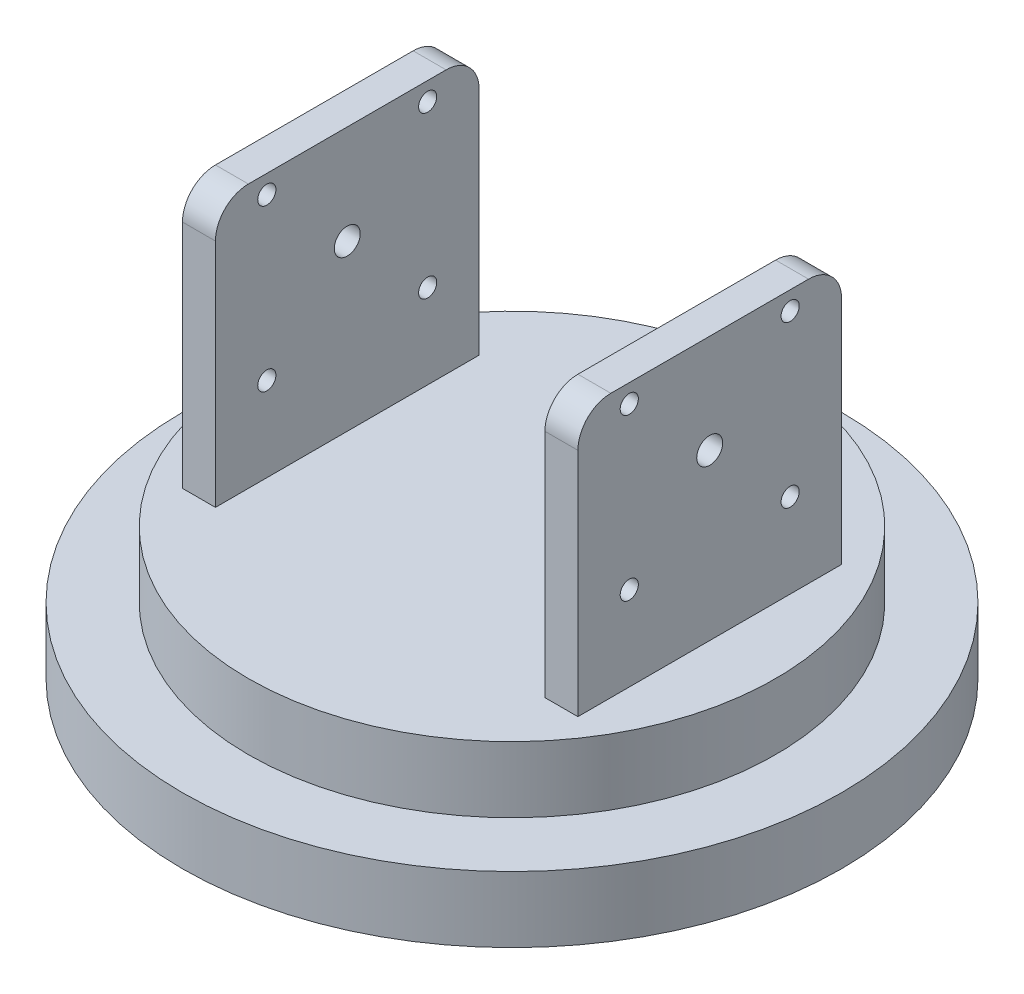
SolidWorks part; units mm, degrees
material "Plain Carbon Steel"
ref_plane "Front Plane" through (0, 0, 0) normal (0, 0, 1) x (1, 0, 0)
ref_plane "Top Plane" through (0, 0, 0) normal (0, 1, 0) x (1, 0, 0)
ref_plane "Right Plane" through (0, 0, 0) normal (1, 0, 0) x (0, 0, -1)
sketch "Sketch2" plane through (0, 0, 0) normal (0, 1, 0) x (1, 0, 0)
  circle A1 centre (0, 0) radius 63.5
  dimension "D2" = 127
extrude "Boss-Extrude1" add sketch "Sketch2" along normal blind 12.7
sketch "Sketch3" plane through (0, 12.7, 0) normal (0, 1, 0) x (1, 0, 0)
  circle A0 centre (0, 0) radius 50.8
  dimension "D1" = 101.6
extrude "Boss-Extrude2" add sketch "Sketch3" along normal blind 12.7
sketch "Sketch4" plane through (0, 0, 0) normal (0, -1, 0) x (1, 0, 0)
  circle A0 centre (0, 0) radius 6.35
  dimension "D1" = 12.7
extrude "Boss-Extrude3" add sketch "Sketch4" along normal blind 25.4
sketch "Sketch5" plane through (0, 25.4, 0) normal (0, 1, 0) x (1, 0, 0)
  line L0 (0, 0) -> (0, 17.7689) construction
  line L1 (38.1, -25.4) -> (31.75, -25.4)
  line L2 (-38.1, 25.4) -> (-31.75, 25.4)
  line L3 (-38.1, 25.4) -> (-38.1, -25.4)
  line L4 (-38.1, -25.4) -> (-31.75, -25.4)
  line L5 (-31.75, 25.4) -> (-31.75, -25.4)
  line L6 (31.75, 25.4) -> (31.75, -25.4)
  line L7 (38.1, 25.4) -> (31.75, 25.4)
  line L8 (38.1, 25.4) -> (38.1, -25.4)
  dimension "D1" = 6.35
  dimension "D2" = 50.8
  dimension "D3" = 25.4
  dimension "D4" = 31.75
extrude "Boss-Extrude4" add sketch "Sketch5" along normal blind 50.8
fillet "Fillet1" radius 6.35 4 edges at (34.925, 76.2, 25.4) (-34.925, 76.2, 25.4) (34.925, 76.2, -25.4) (-34.925, 76.2, -25.4)
sketch "Sketch6" plane through (-38.1, 0, 0) normal (-1, 0, 0) x (0, 0, 1)
  line L0 (-19.05, 76.2) -> (19.05, 76.2) construction
  line L1 (25.4, 69.85) -> (25.4, 25.4) construction
  circle A0 centre (0, 57.15) radius 2.5019
  circle A1 centre (-15.5, 41.65) radius 1.75
  circle A2 centre (15.5, 41.65) radius 1.75
  circle A3 centre (15.5, 72.65) radius 1.75
  circle A4 centre (-15.5, 72.65) radius 1.75
  dimension "D1" = 5.0038
  dimension "D2" = 19.05
  dimension "D3" = 25.4
  dimension "D5" = 15.5
  dimension "D6" = 15.5
  dimension "D7" = 3.5
  dimension "D10" = 31
  dimension "D11" = 31
  dimension "D12" = 9.9
  dimension "D8" = 2
  dimension "D9" = 2
extrude "Cut-Extrude1" cut sketch "Sketch6" against normal through all
sketch "Sketch7" plane through (0, -25.4, 0) normal (0, -1, 0) x (1, 0, 0)
  line L7 (0, 0) -> (0, 6.35) construction
  line L8 (0, 5.08) -> (0.7102, 6.3102)
  line L9 (0, 5.08) -> (-0.7102, 6.3102)
  arc A6 (0.7102, 6.3102) -> (-0.7102, 6.3102) centre (0, 0) ccw
  dimension "D1" = 30
  dimension "D2" = 6.35
  dimension "D3" = 1.4205
  dimension "D4" = 1.4205
extrude "Cut-Extrude2" cut sketch "Sketch7" against normal blind 12.7
pattern_circular "CirPattern1" count 28 over 360 about axis through (0, 0, 0) along (0, 1, 0) of "Cut-Extrude2"
